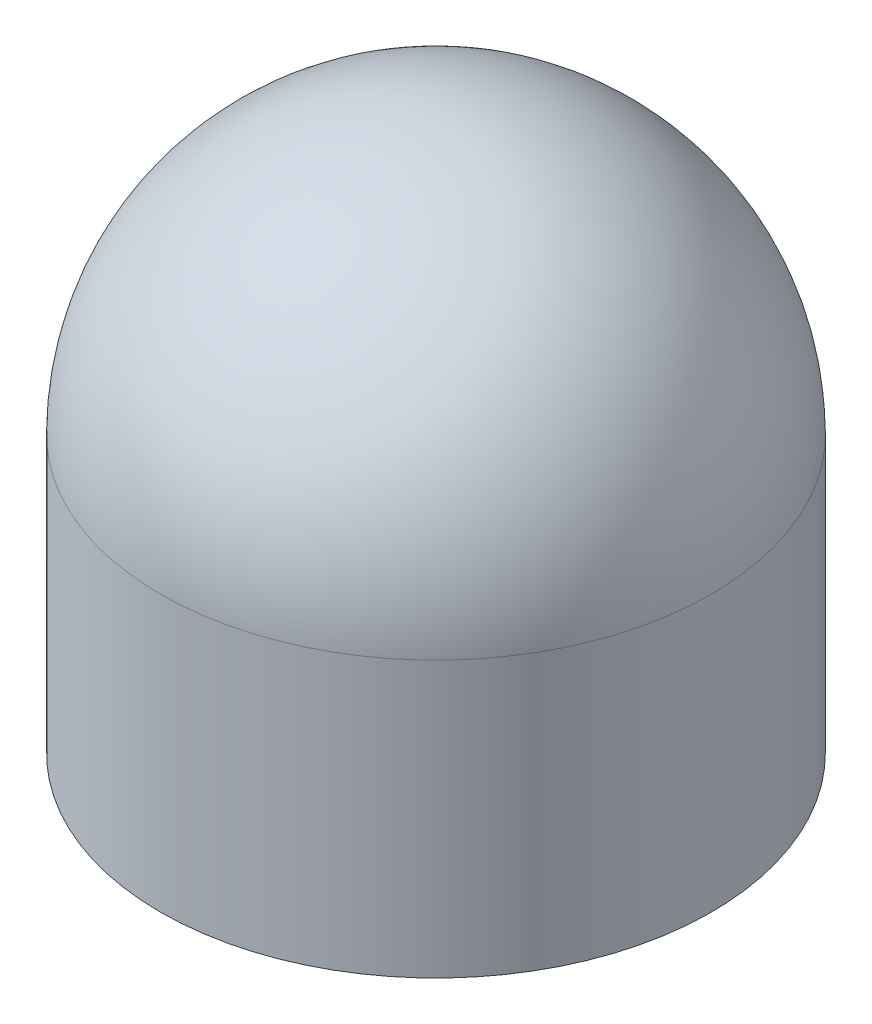
SolidWorks part; units mm, degrees
ref_plane "Front Plane" through (0, 0, 0) normal (0, 0, 1) x (1, 0, 0)
ref_plane "Top Plane" through (0, 0, 0) normal (0, 1, 0) x (1, 0, 0)
ref_plane "Right Plane" through (0, 0, 0) normal (1, 0, 0) x (0, 0, -1)
sketch "Sketch1" plane through (0, 0, 0) normal (1, 0, 0) x (0, 0, -1)
  line L0 (0, 0) -> (0, -68.656) construction
  line L1 (0, 41.2533) -> (0, -41.2533) construction
  line L2 (0, 0) -> (-3.175, 0)
  line L3 (1.8133, 0) -> (-1.8133, 0) construction
  line L4 (-3.175, 0) -> (-3.175, 3.175)
  line L5 (0, 6.35) -> (0, 0)
  arc A0 (-3.175, 3.175) -> (0, 6.35) centre (0, 3.175) cw
  dimension "D1" = 3.175
  dimension "D2" = 6.35
revolve "Revolve2" add sketch "Sketch1" angle 360 about L0
sketch "Sketch2" plane through (0, 0, 0) normal (0, -1, 0) x (1, 0, 0)
  circle A0 centre (0, 0) radius 1.5
  dimension "D1" = 3
extrude "Cut-Extrude1" cut sketch "Sketch2" against normal blind 3.175
